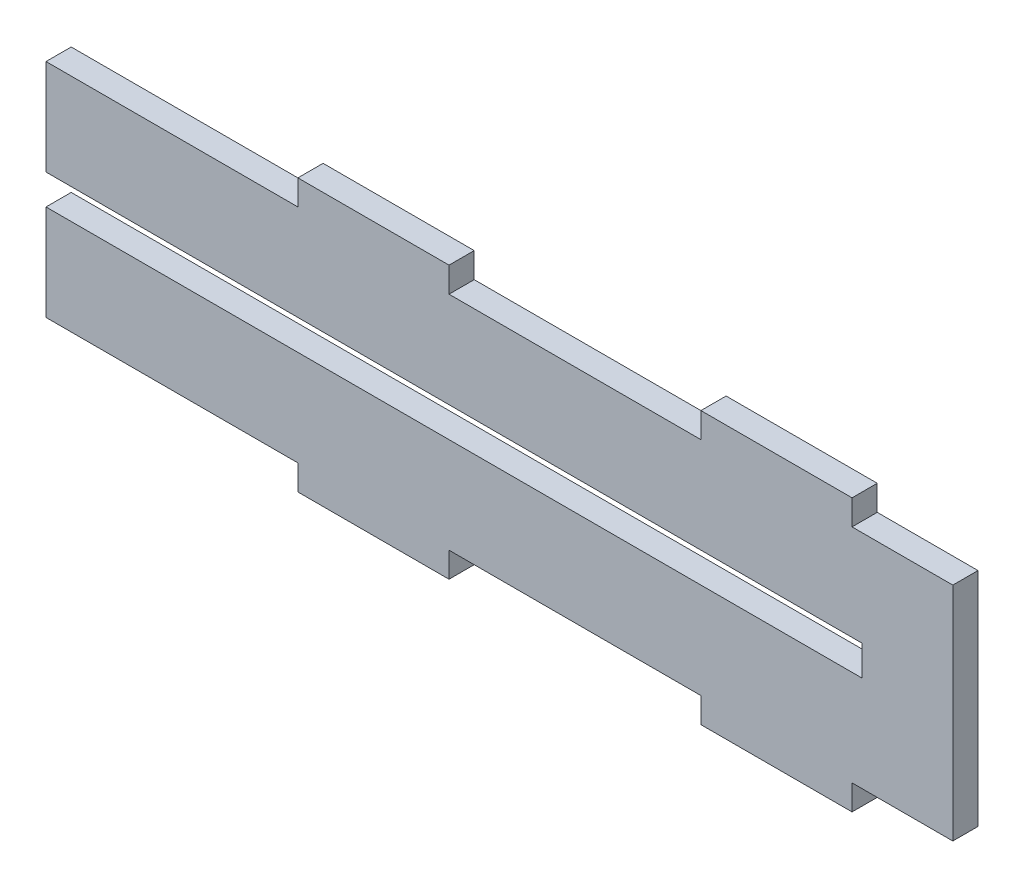
SolidWorks part; units mm, degrees
ref_plane "Plano frontal" through (0, 0, 0) normal (0, 0, 1) x (1, 0, 0)
ref_plane "Plano superior" through (0, 0, 0) normal (0, 1, 0) x (1, 0, 0)
ref_plane "Plano direito" through (0, 0, 0) normal (1, 0, 0) x (0, 0, -1)
sketch "Esboço1" plane through (0, 0, 0) normal (0, 0, 1) x (1, 0, 0)
  line L0 (0, -44) -> (50, -44)
  line L1 (0, 0) -> (50, 0)
  line L2 (0, 0) -> (0, -44)
  line L3 (50, -49) -> (80, -49)
  line L5 (50, -44) -> (50, -49)
  line L6 (80, -49) -> (80, -44)
  line L7 (80, -44) -> (130, -44)
  line L8 (130, -44) -> (130, -49)
  line L9 (160, -49) -> (160, -44)
  line L10 (160, -44) -> (180, -44)
  line L11 (130, -49) -> (160, -49)
  line L12 (0, -22) -> (180, -22) construction
  line L13 (0, 0) -> (50, 0)
  line L14 (80, 0) -> (130, 0)
  line L15 (160, 0) -> (180, 0)
  line L16 (160, 5) -> (160, 0)
  line L17 (130, 5) -> (160, 5)
  line L18 (130, 0) -> (130, 5)
  line L19 (80, 5) -> (80, 0)
  line L20 (50, 5) -> (80, 5)
  line L21 (50, 0) -> (50, 5)
  line L22 (80, 0) -> (130, 0)
  line L23 (160, 0) -> (180, 0)
  line L24 (180, 0) -> (180, -44)
  line L25 (0, -19) -> (162, -19)
  line L26 (0, -19) -> (0, -25)
  line L27 (0, -25) -> (162, -25)
  line L28 (162, -19) -> (162, -25)
  point P27 (0, -22)
  dimension "D2" = 44
  dimension "D3" = 50
  dimension "D4" = 5
  dimension "D5" = 30
  dimension "D6" = 50
  dimension "D7" = 5
  dimension "D8" = 30
  dimension "D9" = 5
  dimension "D10" = 180
  dimension "D11" = 162
  dimension "D12" = 6
  dimension "D14" = 30
extrude "Ressalto-extrusão1" add sketch "Esboço1" along normal blind 5
